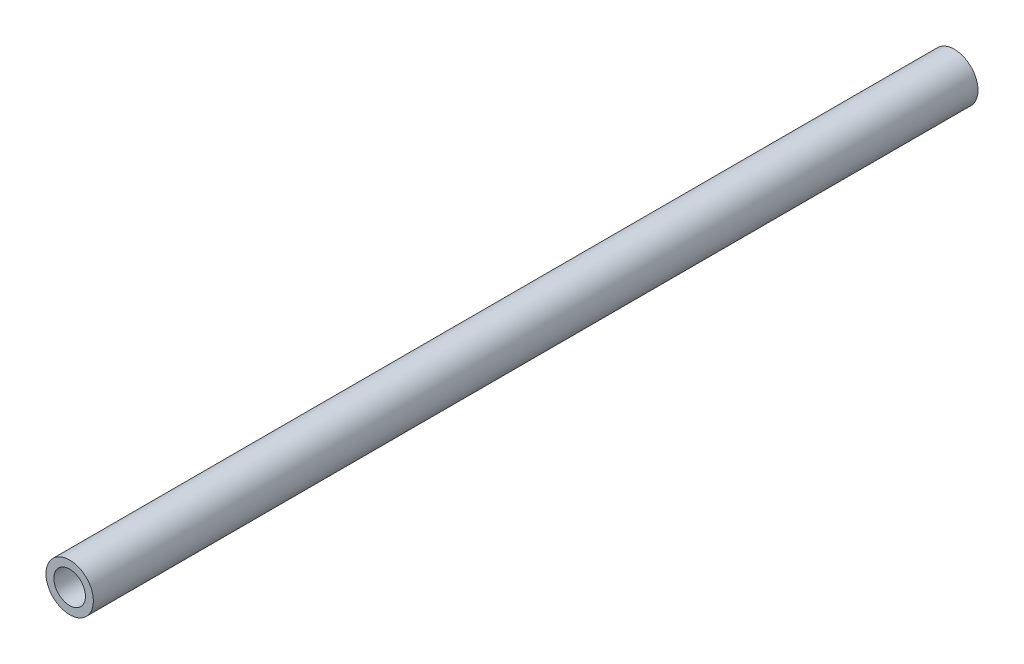
SolidWorks part; units mm, degrees
ref_plane "Front Plane" through (0, 0, 0) normal (0, 0, 1) x (1, 0, 0)
ref_plane "Top Plane" through (0, 0, 0) normal (0, 1, 0) x (1, 0, 0)
ref_plane "Right Plane" through (0, 0, 0) normal (1, 0, 0) x (0, 0, -1)
sketch "Sketch1" plane through (0, 0, 0) normal (0, 0, 1) x (1, 0, 0)
  circle A0 centre (0, 0) radius 5
  circle A1 centre (0, 0) radius 7.5
  dimension "D1" = 10
  dimension "D2" = 15
extrude "Boss-Extrude1" add sketch "Sketch1" along normal blind 280
